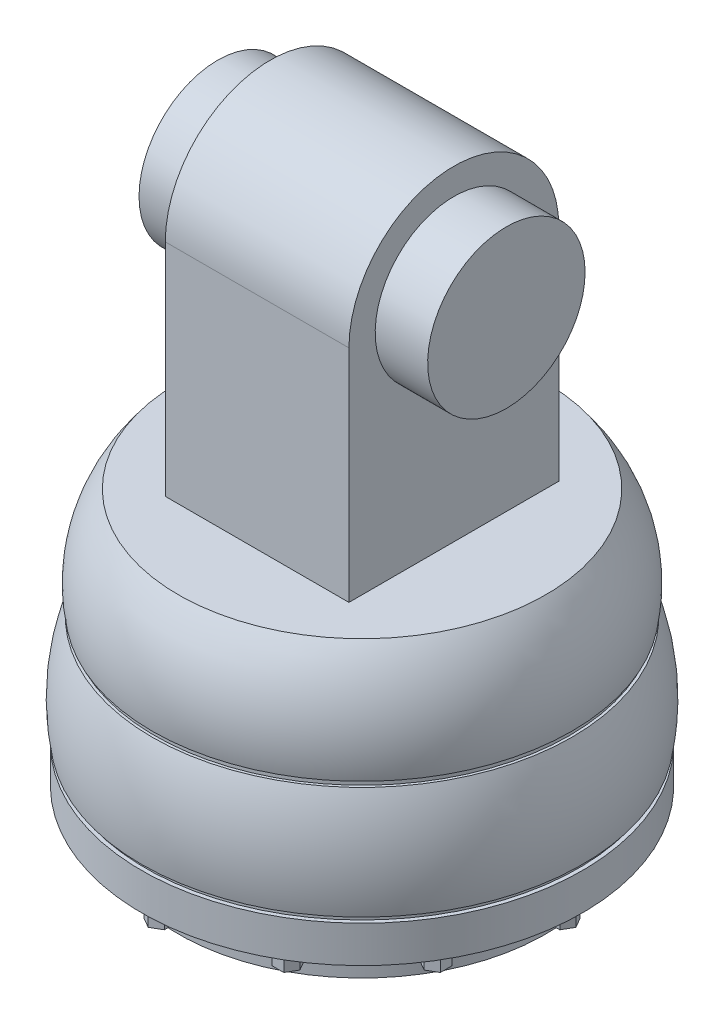
SolidWorks part; units mm, degrees
ref_plane "Plan de face" through (0, 0, 0) normal (0, 0, 1) x (1, 0, 0)
ref_plane "Plan de dessus" through (0, 0, 0) normal (0, 1, 0) x (1, 0, 0)
ref_plane "Plan de droite" through (0, 0, 0) normal (1, 0, 0) x (0, 0, -1)
sketch "Esquisse1" plane through (0, 0, 0) normal (0, 0, 1) x (1, 0, 0)
  line L0 (-35, 0) -> (0, 0)
  line L1 (0, 0) -> (0, -20)
  line L2 (0, -20) -> (-40, -20)
  arc A0 (-35, 0) -> (-40, -20) centre (-15.404, -15.524) ccw
  dimension "D4" = 25
  dimension "D1" = 35
  dimension "D2" = 20
  dimension "D3" = 40
revolve "Révolution1" add sketch "Esquisse1" angle 360 about L1
sketch "Esquisse2" plane through (0, -20, 0) normal (0, -1, 0) x (1, 0, 0)
  circle A0 centre (0, 0) radius 39.5
  dimension "D1" = 79
extrude "Boss.-Extru.1" add sketch "Esquisse2" along normal blind 1
sketch "Esquisse3" plane through (0, 0, 0) normal (1, 0, 0) x (0, 0, -1)
  line L0 (0, -21) -> (-40, -21)
  line L1 (-39.5, -21) -> (39.5, -21) construction
  line L2 (0, -21) -> (0, -41)
  line L3 (0, -41) -> (-42, -41)
  arc A0 (-42, -41) -> (-40, -21) centre (-5.5677, -34.5432) cw
  dimension "D4" = 37
  dimension "D1" = 40
  dimension "D2" = 20
  dimension "D3" = 42
revolve "Révolution2" add sketch "Esquisse3" angle 360 about L2
sketch "Esquisse4" plane through (0, -41, 0) normal (0, -1, 0) x (1, 0, 0)
  circle A0 centre (0, 0) radius 41.25
  dimension "D1" = 82.5
extrude "Boss.-Extru.2" add sketch "Esquisse4" along normal blind 1
sketch "Esquisse5" plane through (0, -42, 0) normal (0, -1, 0) x (1, 0, 0)
  circle A0 centre (0, 0) radius 42
  dimension "D1" = 84
extrude "Boss.-Extru.3" add sketch "Esquisse5" along normal blind 7
sketch "Esquisse6" plane through (0, -49, 0) normal (0, -1, 0) x (1, 0, 0)
  circle A0 centre (0, 0) radius 35
  dimension "D1" = 70
extrude "Boss.-Extru.4" add sketch "Esquisse6" along normal blind 7
sketch "Esquisse7" plane through (0, -49, 0) normal (0, -1, 0) x (1, 0, 0)
  line L0 (35, 0) -> (42, 0) construction
  line L1 (39.5953, 0) -> (39.0476, 0.9486)
  line L2 (40.75, 0) -> (39.625, 1.9486)
  line L3 (39.625, 1.9486) -> (37.375, 1.9486)
  line L4 (37.375, 1.9486) -> (36.25, 0)
  line L5 (36.25, 0) -> (37.375, -1.9486)
  line L6 (37.375, -1.9486) -> (39.625, -1.9486)
  line L7 (39.625, -1.9486) -> (40.75, 0)
  line L8 (39.0476, 0.9486) -> (37.9524, 0.9486)
  line L9 (37.9524, 0.9486) -> (37.4047, 0)
  line L10 (37.4047, 0) -> (37.9524, -0.9486)
  line L11 (37.9524, -0.9486) -> (39.0476, -0.9486)
  line L12 (39.0476, -0.9486) -> (39.5953, 0)
  circle A0 centre (0, 0) radius 35 construction
  circle A1 centre (0, 0) radius 35 construction
  circle A2 centre (0, 0) radius 42 construction
  circle A3 centre (38.5, 0) radius 1.9486 construction
  dimension "D1" = 4.5
  dimension "D2" = 1
extrude "Boss.-Extru.5" add sketch "Esquisse7" along normal blind 3
pattern_circular "Répétition circulaire1" count 12 over 360 about axis through (0, 0, 0) along (0, 1, 0) of "Boss.-Extru.5"
sketch "Esquisse8" plane through (0, -56, 0) normal (0, -1, 0) x (1, 0, 0)
  circle A0 centre (0, 0) radius 15
  dimension "D1" = 30
extrude "Boss.-Extru.6" add sketch "Esquisse8" along normal blind 10
sketch "Esquisse9" plane through (0, 0, 0) normal (0, 1, 0) x (1, 0, 0)
  line L1 (-17.5, -20) -> (17.5, -20)
  line L2 (-17.5, -20) -> (-17.5, 20)
  line L3 (-17.5, 20) -> (17.5, 20)
  line L4 (17.5, -20) -> (17.5, 20)
  line L5 (-17.5, -20) -> (17.5, 20) construction
  line L6 (-17.5, 20) -> (17.5, -20) construction
  point P0 (0, 0)
  dimension "D1" = 35
  dimension "D2" = 40
extrude "Boss.-Extru.7" add sketch "Esquisse9" along normal blind 42
sketch "Esquisse10" plane through (-17.5, 0, 0) normal (-1, 0, 0) x (0, 0, 1)
  line L0 (-20, 42) -> (20, 42) construction
  line L1 (-20, 42) -> (20.6175, 42)
  line L2 (20.6175, 42) -> (20, 42)
  arc A0 (20, 42) -> (-20, 42) centre (0, 42) ccw
  line M3 (20, 42) -> (-20, 42)
extrude "Boss.-Extru.8" add sketch "Esquisse10" along direction (-1, 0, 0) on the side against the normal blind 35 contours A0 M3
sketch "Esquisse11" plane through (-17.5, 0, 0) normal (-1, 0, 0) x (0, 0, 1)
  circle A0 centre (0, 42) radius 15
  dimension "D1" = 30
extrude "Boss.-Extru.9" add sketch "Esquisse11" along normal blind 10
sketch "Esquisse12" plane through (17.5, 0, 0) normal (1, 0, 0) x (0, 0, -1)
  circle A0 centre (0, 42) radius 15
  dimension "D1" = 30
extrude "Boss.-Extru.10" add sketch "Esquisse12" along normal blind 10
